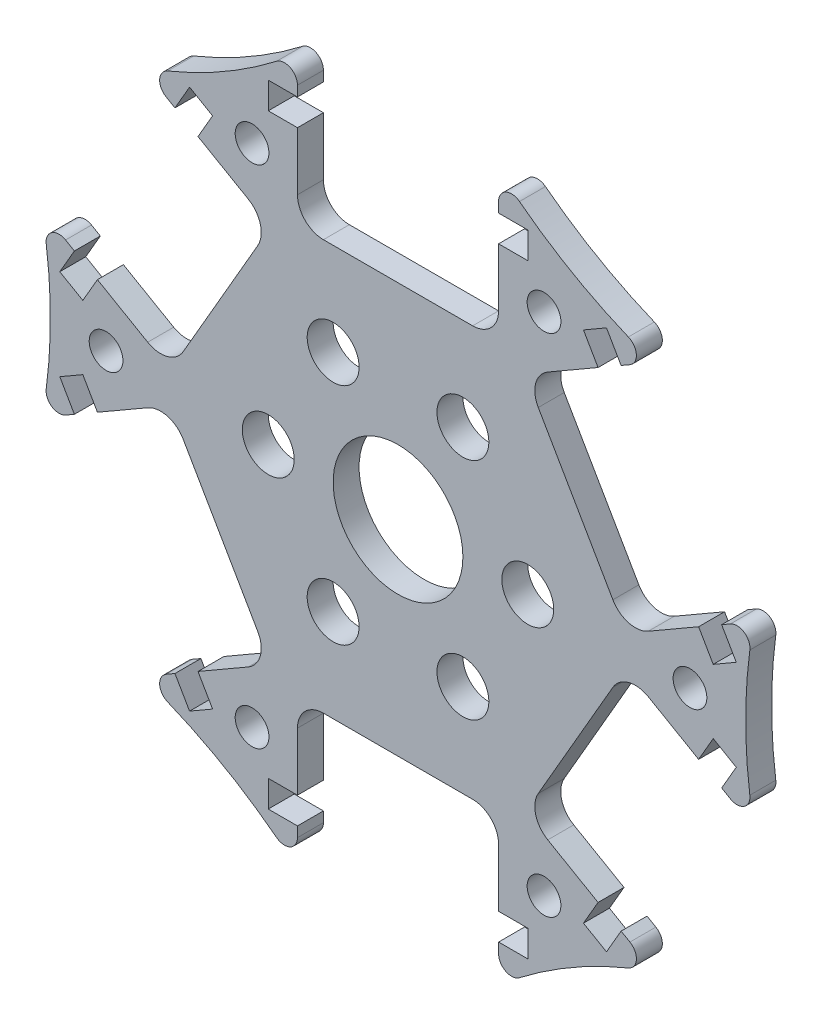
SolidWorks part; units mm, degrees
material "6061 合金"
ref_plane "Front" through (0, 0, 0) normal (0, 0, 1) x (1, 0, 0)
ref_plane "Top" through (0, 0, 0) normal (0, 1, 0) x (1, 0, 0)
ref_plane "Right" through (0, 0, 0) normal (1, 0, 0) x (0, 0, -1)
sketch "ｽｹｯﾁ1" plane through (0, 0, 0) normal (0, 0, 1) x (1, 0, 0)
  circle A0 centre (0, 0) radius 28.3
  dimension "D1" = 56.6
extrude "ﾎﾞｽ - 押し出し1" add sketch "ｽｹｯﾁ1" along normal blind 2
sketch "ｽｹｯﾁ2" plane through (0, 0, 2) normal (0, 0, 1) x (1, 0, 0)
  line L0 (0, 0) -> (0, 50000) construction
  line L1 (7.75, 24.325) -> (10, 24.325)
  line L2 (10, 24.325) -> (10, 22.275)
  line L3 (-7.75, 15.8) -> (-7.75, 22.275)
  line L4 (10, 22.275) -> (7.75, 22.275)
  line L5 (7.75, 27.2181) -> (7.75, 24.325)
  line L6 (7.75, 22.275) -> (7.75, 15.8)
  line L7 (7.75, 15.8) -> (-7.75, 15.8)
  line L8 (-7.75, 22.275) -> (-10, 22.275)
  line L9 (-10, 22.275) -> (-10, 24.325)
  line L10 (-10, 24.325) -> (-7.75, 24.325)
  line L11 (-7.75, 24.325) -> (-7.75, 27.2181)
  line L12 (0, 28.3) -> (16.8233, 28.3) construction
  line L13 (10, 23.3) -> (-10, 23.3) construction
  line L14 (0, 0) -> (28.3, 0) construction
  line L15 (24.9411, 5.4508) -> (26.0661, 3.5022)
  line L16 (26.0661, 3.5022) -> (24.2907, 2.4772)
  line L17 (9.8082, 14.6117) -> (15.4157, 17.8492)
  line L18 (24.2907, 2.4772) -> (23.1657, 4.4258)
  line L19 (27.4466, 6.8974) -> (24.9411, 5.4508)
  line L20 (23.1657, 4.4258) -> (17.5582, 1.1883)
  line L21 (17.5582, 1.1883) -> (9.8082, 14.6117)
  line L22 (15.4157, 17.8492) -> (14.2907, 19.7978)
  line L23 (14.2907, 19.7978) -> (16.0661, 20.8228)
  line L24 (16.0661, 20.8228) -> (17.1911, 18.8742)
  line L25 (17.1911, 18.8742) -> (19.6966, 20.3208)
  line L26 (25.1784, 2.9897) -> (15.1784, 20.3103) construction
  line L27 (17.1911, -18.8742) -> (16.0661, -20.8228)
  line L28 (16.0661, -20.8228) -> (14.2907, -19.7978)
  line L29 (17.5582, -1.1883) -> (23.1657, -4.4258)
  line L30 (14.2907, -19.7978) -> (15.4157, -17.8492)
  line L31 (19.6966, -20.3208) -> (17.1911, -18.8742)
  line L32 (15.4157, -17.8492) -> (9.8082, -14.6117)
  line L33 (9.8082, -14.6117) -> (17.5582, -1.1883)
  line L34 (23.1657, -4.4258) -> (24.2907, -2.4772)
  line L35 (24.2907, -2.4772) -> (26.0661, -3.5022)
  line L36 (26.0661, -3.5022) -> (24.9411, -5.4508)
  line L37 (24.9411, -5.4508) -> (27.4466, -6.8974)
  line L38 (15.1784, -20.3103) -> (25.1784, -2.9897) construction
  line L39 (-7.75, -24.325) -> (-10, -24.325)
  line L40 (-10, -24.325) -> (-10, -22.275)
  line L41 (7.75, -15.8) -> (7.75, -22.275)
  line L42 (-10, -22.275) -> (-7.75, -22.275)
  line L43 (-7.75, -27.2181) -> (-7.75, -24.325)
  line L44 (-7.75, -22.275) -> (-7.75, -15.8)
  line L45 (-7.75, -15.8) -> (7.75, -15.8)
  line L46 (7.75, -22.275) -> (10, -22.275)
  line L47 (10, -22.275) -> (10, -24.325)
  line L48 (10, -24.325) -> (7.75, -24.325)
  line L49 (7.75, -24.325) -> (7.75, -27.2181)
  line L50 (-10, -23.3) -> (10, -23.3) construction
  line L51 (-24.9411, -5.4508) -> (-26.0661, -3.5022)
  line L52 (-26.0661, -3.5022) -> (-24.2907, -2.4772)
  line L53 (-9.8082, -14.6117) -> (-15.4157, -17.8492)
  line L54 (-24.2907, -2.4772) -> (-23.1657, -4.4258)
  line L55 (-27.4466, -6.8974) -> (-24.9411, -5.4508)
  line L56 (-23.1657, -4.4258) -> (-17.5582, -1.1883)
  line L57 (-17.5582, -1.1883) -> (-9.8082, -14.6117)
  line L58 (-15.4157, -17.8492) -> (-14.2907, -19.7978)
  line L59 (-14.2907, -19.7978) -> (-16.0661, -20.8228)
  line L60 (-16.0661, -20.8228) -> (-17.1911, -18.8742)
  line L61 (-17.1911, -18.8742) -> (-19.6966, -20.3208)
  line L62 (-25.1784, -2.9897) -> (-15.1784, -20.3103) construction
  line L63 (-17.1911, 18.8742) -> (-16.0661, 20.8228)
  line L64 (-16.0661, 20.8228) -> (-14.2907, 19.7978)
  line L65 (-17.5582, 1.1883) -> (-23.1657, 4.4258)
  line L66 (-14.2907, 19.7978) -> (-15.4157, 17.8492)
  line L67 (-19.6966, 20.3208) -> (-17.1911, 18.8742)
  line L68 (-15.4157, 17.8492) -> (-9.8082, 14.6117)
  line L69 (-9.8082, 14.6117) -> (-17.5582, 1.1883)
  line L70 (-23.1657, 4.4258) -> (-24.2907, 2.4772)
  line L71 (-24.2907, 2.4772) -> (-26.0661, 3.5022)
  line L72 (-26.0661, 3.5022) -> (-24.9411, 5.4508)
  line L73 (-24.9411, 5.4508) -> (-27.4466, 6.8974)
  line L74 (-15.1784, 20.3103) -> (-25.1784, 2.9897) construction
  line L75 (0, 0) -> (5, 8.6603) construction
  line L76 (0, 0) -> (11.25, 19.4856) construction
  arc A0 (7.75, 27.2181) -> (-7.75, 27.2181) centre (0, 0) ccw
  circle A1 centre (0, 0) radius 28.3 construction
  circle A2 centre (0, 0) radius 5
  circle A3 centre (0, 0) radius 10 construction
  arc A4 (27.4466, 6.8974) -> (19.6966, 20.3208) centre (0, 0) ccw
  arc A5 (19.6966, -20.3208) -> (27.4466, -6.8974) centre (0, 0) ccw
  arc A6 (-7.75, -27.2181) -> (7.75, -27.2181) centre (0, 0) ccw
  arc A7 (-27.4466, -6.8974) -> (-19.6966, -20.3208) centre (0, 0) ccw
  arc A8 (-19.6966, 20.3208) -> (-27.4466, 6.8974) centre (0, 0) ccw
  circle A9 centre (5, 8.6603) radius 2
  circle A10 centre (10, 0) radius 2
  circle A11 centre (5, -8.6603) radius 2
  circle A12 centre (-5, -8.6603) radius 2
  circle A13 centre (-10, 0) radius 2
  circle A14 centre (-5, 8.6603) radius 2
  circle A15 centre (0, 0) radius 22.5 construction
  circle A16 centre (11.25, 19.4856) radius 1.3
  circle A17 centre (22.5, 0) radius 1.3
  circle A18 centre (11.25, -19.4856) radius 1.3
  circle A19 centre (-11.25, -19.4856) radius 1.3
  circle A20 centre (-22.5, 0) radius 1.3
  circle A21 centre (-11.25, 19.4856) radius 1.3
  point P99 (0, 0)
  point P111 (0, 0)
  dimension "D1" = 15.5
  dimension "D6" = 10
  dimension "D7" = 20
  dimension "D9" = 60
  dimension "D10" = 4
  dimension "D12" = 45
  dimension "D13" = 2.6
  dimension "D2" = 20
  dimension "D3" = 2.05
  dimension "D4" = 12.5
  dimension "D5" = 5
  dimension "D8" = 6
  dimension "D11" = 6
extrude "ｶｯﾄ - 押し出し1" cut sketch "ｽｹｯﾁ2" against normal through all
sketch "ｽｹｯﾁ3" plane through (0, 0, 2) normal (0, 0, 1) x (1, 0, 0)
  line L0 (0, 0) -> (14.15, 24.5085) construction
  arc A0 (19.6966, 20.3208) -> (7.75, 27.2181) centre (0, 0) ccw construction
  arc A1 (7.75, 27.2181) -> (19.6966, 20.3208) centre (31.65, 54.8194) ccw
  arc A2 (19.6966, 20.3208) -> (7.75, 27.2181) centre (0, 0) ccw
  arc A3 (27.4466, 6.8974) -> (27.4466, -6.8974) centre (63.3, 0) ccw
  arc A4 (27.4466, -6.8974) -> (27.4466, 6.8974) centre (0, 0) ccw
  arc A5 (19.6966, -20.3208) -> (7.75, -27.2181) centre (31.65, -54.8194) ccw
  arc A6 (7.75, -27.2181) -> (19.6966, -20.3208) centre (0, 0) ccw
  arc A7 (-7.75, -27.2181) -> (-19.6966, -20.3208) centre (-31.65, -54.8194) ccw
  arc A8 (-19.6966, -20.3208) -> (-7.75, -27.2181) centre (0, 0) ccw
  arc A9 (-27.4466, -6.8974) -> (-27.4466, 6.8974) centre (-63.3, 0) ccw
  arc A10 (-27.4466, 6.8974) -> (-27.4466, -6.8974) centre (0, 0) ccw
  arc A11 (-19.6966, 20.3208) -> (-7.75, 27.2181) centre (-31.65, 54.8194) ccw
  arc A12 (-7.75, 27.2181) -> (-19.6966, 20.3208) centre (0, 0) ccw
  point P27 (0, 0)
  dimension "D1" = 35
  dimension "D2" = 6
extrude "ｶｯﾄ - 押し出し3" cut sketch "ｽｹｯﾁ3" against normal through all
fillet "ﾌｨﾚｯﾄ2" radius 2 12 edges at (-9.8082, 14.6117, 1) (-17.5582, -1.1883, 1) (-17.5582, 1.1883, 1) (-7.75, -15.8, 1) (-9.8082, -14.6117, 1) (9.8082, -14.6117, 1) (7.75, -15.8, 1) (17.5582, -1.1883, 1) (17.5582, 1.1883, 1) (9.8082, 14.6117, 1) (7.75, 15.8, 1) (-7.75, 15.8, 1)
fillet "ﾌｨﾚｯﾄ1" radius 1 12 edges at (19.6966, 20.3208, 1) (7.75, 27.2181, 1) (-19.6966, 20.3208, 1) (-7.75, 27.2181, 1) (-27.4466, 6.8974, 1) (-27.4466, -6.8974, 1) (-19.6966, -20.3208, 1) (-7.75, -27.2181, 1) (7.75, -27.2181, 1) (19.6966, -20.3208, 1) (27.4466, -6.8974, 1) (27.4466, 6.8974, 1)
